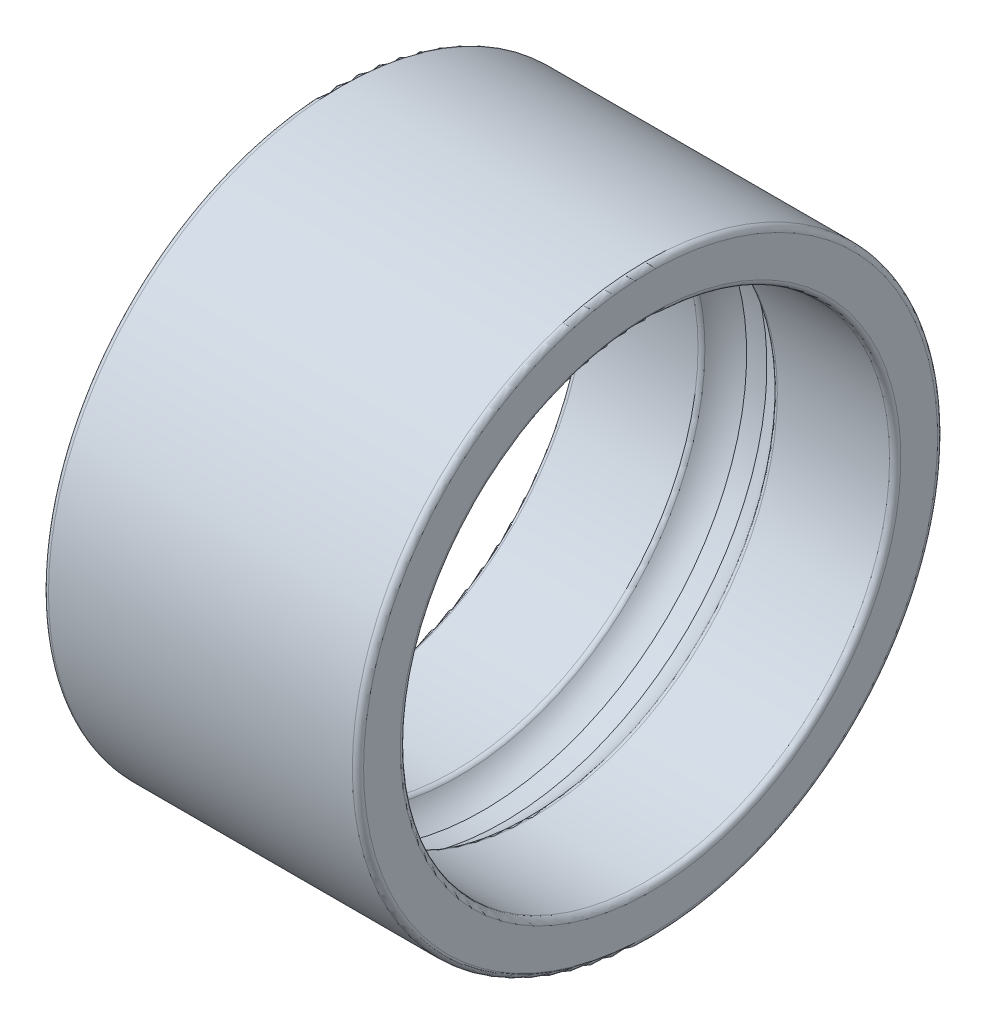
SolidWorks part; units mm, degrees
material "Chrome Stainless Steel"
ref_plane "Front Plane" through (0, 0, 0) normal (0, 0, 1) x (1, 0, 0)
ref_plane "Top Plane" through (0, 0, 0) normal (0, 1, 0) x (1, 0, 0)
ref_plane "Right Plane" through (0, 0, 0) normal (1, 0, 0) x (0, 0, -1)
sketch "Sketch1" plane through (0, 0, 0) normal (0, 0, 1) x (1, 0, 0)
  line L0 (0, 0) -> (25.2899, 0) construction
  line L1 (0, 10.87) -> (0, 13)
  line L2 (0, 13) -> (14, 13)
  line L3 (14, 13) -> (14, 10.87)
  line L4 (14, 10.87) -> (8.6288, 10.87)
  line L5 (7.45, 11.72) -> (6.55, 11.72)
  line L6 (7, 13) -> (7, 11.72) construction
  line L7 (0, 10.87) -> (5.3712, 10.87)
  arc A0 (8.6288, 10.87) -> (7.45, 11.72) centre (7, 9.8535) ccw
  arc A1 (5.3712, 10.87) -> (6.55, 11.72) centre (7, 9.8535) cw
  dimension "D1" = 26
  dimension "D5" = 1.92
  dimension "D2" = 14
  dimension "D3" = 2.13
  dimension "D4" = 0.9
  dimension "D6" = 1.28
revolve "Revolve1" add sketch "Sketch1" angle 360 about L0
fillet "Fillet1" radius 0.25 6 edges at (5.3712, 0, 10.87) (8.6288, 0, 10.87) (14, 0, 10.87) (0, 0, 10.87) (0, 0, 13) (14, 0, 13)
